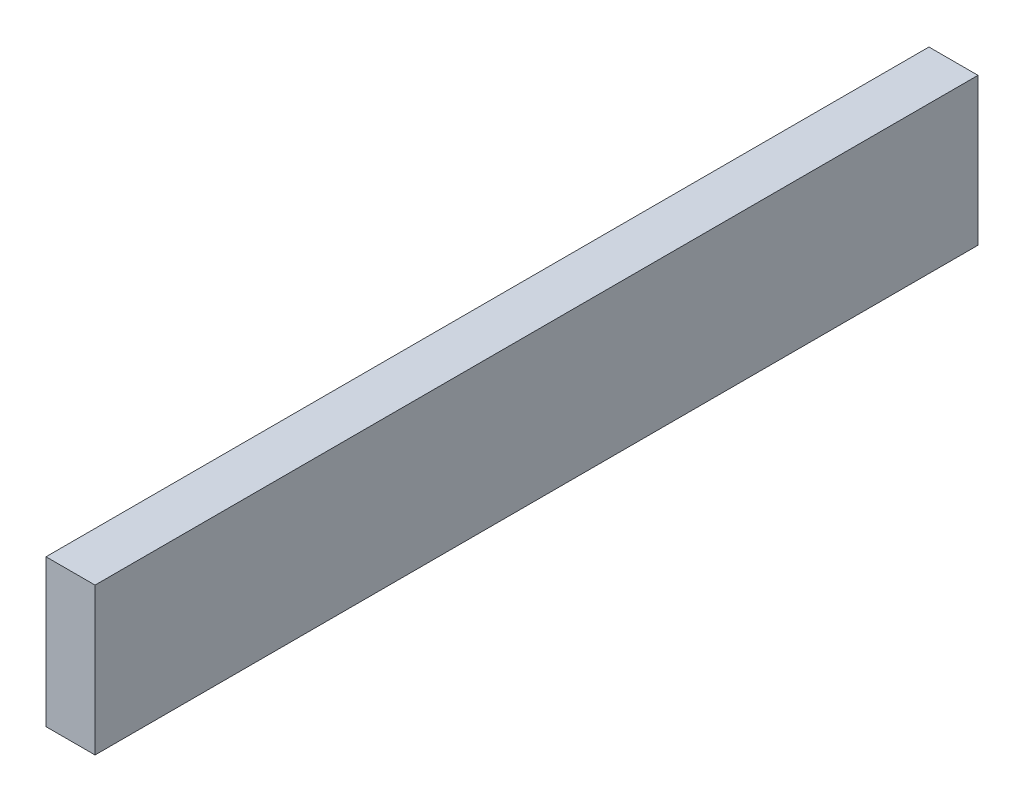
SolidWorks part; units mm, degrees
ref_plane "Front Plane" through (0, 0, 0) normal (0, 0, 1) x (1, 0, 0)
ref_plane "Top Plane" through (0, 0, 0) normal (0, 1, 0) x (1, 0, 0)
ref_plane "Right Plane" through (0, 0, 0) normal (1, 0, 0) x (0, 0, -1)
sketch "Sketch1" plane through (0, 0, 0) normal (0, 0, 1) x (1, 0, 0)
  line L1 (-25.4, 76.2) -> (25.4, 76.2)
  line L2 (-25.4, 76.2) -> (-25.4, -76.2)
  line L3 (-25.4, -76.2) -> (25.4, -76.2)
  line L4 (25.4, 76.2) -> (25.4, -76.2)
  line L5 (0, -76.2) -> (0, 76.2) construction
  line L6 (-25.4, 0) -> (25.4, 0) construction
  point P0 (0, 0)
  dimension "D1" = 152.4
  dimension "D2" = 50.8
extrude "Boss-Extrude1" add sketch "Sketch1" against normal blind 914.4
